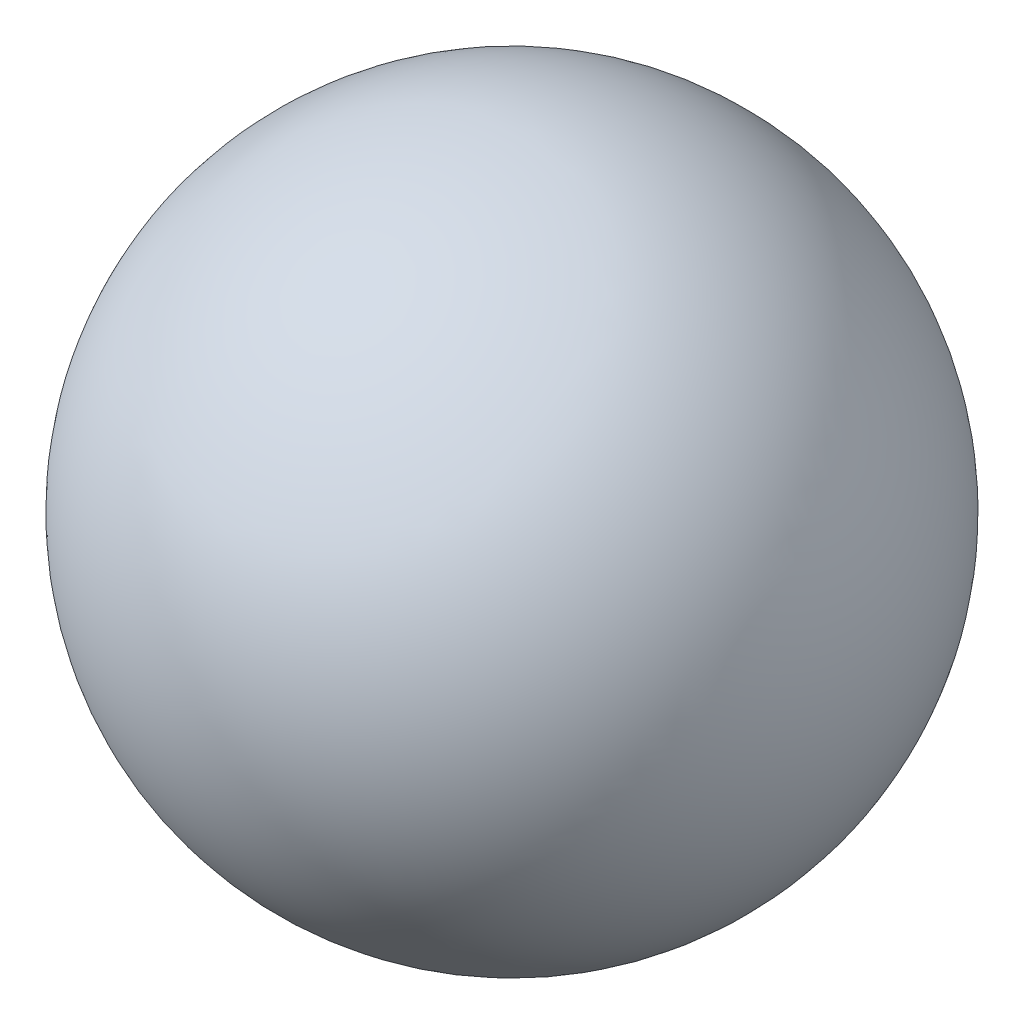
SolidWorks part; units mm, degrees
material "Cast Stainless Steel"
ref_plane "Front Plane" through (0, 0, 0) normal (0, 0, 1) x (1, 0, 0)
ref_plane "Top Plane" through (0, 0, 0) normal (0, 1, 0) x (1, 0, 0)
ref_plane "Right Plane" through (0, 0, 0) normal (1, 0, 0) x (0, 0, -1)
sketch "Sketch1" plane through (0, 0, 0) normal (0, 0, 1) x (1, 0, 0)
  line L0 (-8, 0) -> (8, 0)
  arc A0 (8, 0) -> (-8, 0) centre (0, 0) ccw
  dimension "D1" = 16
revolve "Revolve1" add sketch "Sketch1" angle 360 about L0
ref_plane "Plane1" through (0, 9, 0) normal (0, 1, 0) x (1, 0, 0)
sketch "Sketch3" plane through (0, 9, 0) normal (0, 1, 0) x (1, 0, 0)
  circle A0 centre (0, 0) radius 9
